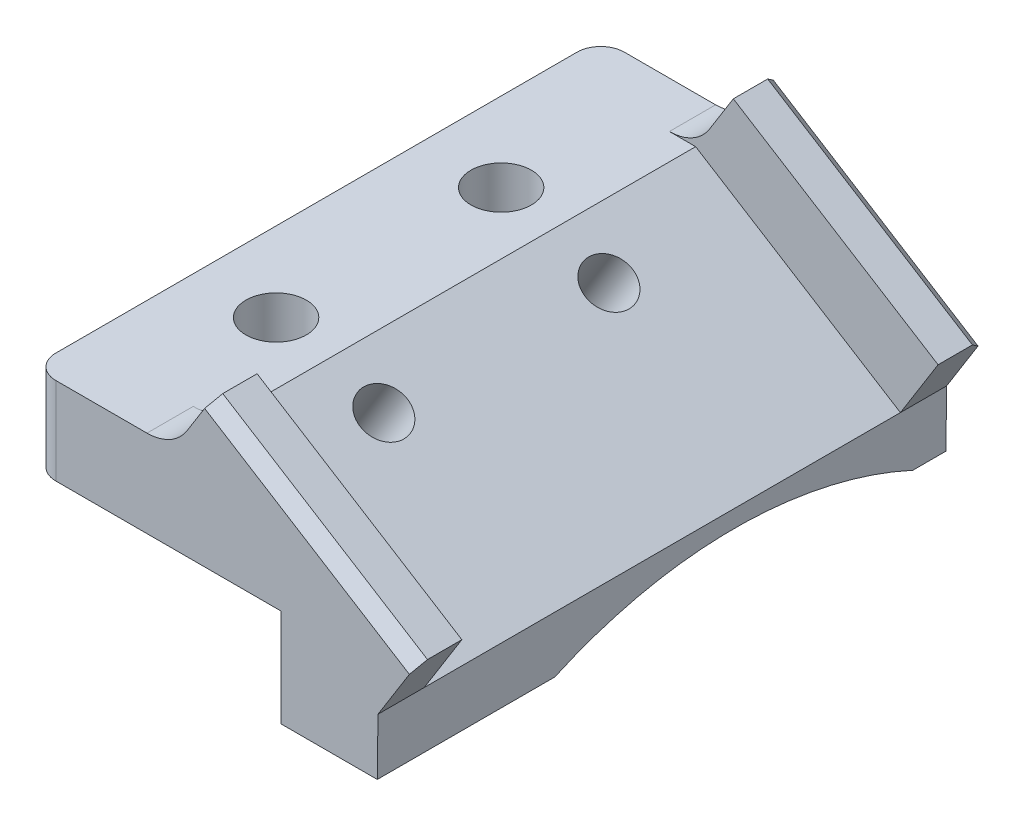
SolidWorks part; units mm, degrees
ref_plane "Front Plane" through (0, 0, 0) normal (0, 0, 1) x (1, 0, 0)
ref_plane "Top Plane" through (0, 0, 0) normal (0, 1, 0) x (1, 0, 0)
ref_plane "Right Plane" through (0, 0, 0) normal (1, 0, 0) x (0, 0, -1)
sketch "Sketch2" plane through (0, 0, 0) normal (0, 0, 1) x (1, 0, 0)
  line L0 (-14.571, 4.125) -> (-4.071, 4.125)
  line L1 (-4.071, 4.125) -> (-4.071, 0)
  line L2 (-4.071, 0) -> (0, 0)
  line L3 (0, 0) -> (0.0293, 2.4)
  line L4 (0.0293, 2.4) -> (-8.6125, 7.8)
  line L5 (-8.6125, 7.8) -> (-14.571, 7.8)
  line L6 (-14.571, 7.8) -> (-14.571, 4.125)
  dimension "D1" = 0.7
  dimension "D2" = 4.071
  dimension "D3" = 10.5
  dimension "D4" = 4.125
  dimension "D5" = 32
  dimension "D6" = 7.8
  dimension "D7" = 2.4
extrude "Boss-Extrude1" add sketch "Sketch2" along normal blind 24
sketch "Sketch3" plane through (1.0868, 1.7392, 0) normal (0.5299, 0.848, 0) x (0.848, -0.5299, 0)
  line L0 (-1.2469, -24) -> (-1.2469, 0) construction
  line L1 (-11.4372, 0) -> (-1.2469, 0)
  line L2 (-11.4372, 0) -> (-11.4372, -1.95)
  line L3 (-11.4372, -1.95) -> (-1.2469, -1.95)
  line L4 (-1.2469, 0) -> (-1.2469, -1.95)
  line L6 (-11.4372, -24) -> (-1.2469, -24)
  line L7 (-11.4372, -24) -> (-11.4372, -22.05)
  line L8 (-11.4372, -22.05) -> (-1.2469, -22.05)
  line L9 (-1.2469, -24) -> (-1.2469, -22.05)
  dimension "D1" = 20.1
  dimension "D2" = 1.95
  dimension "D3" = 1.95
extrude "Boss-Extrude2" add sketch "Sketch3" along normal blind 3
sketch "Sketch5" plane through (0, 0, 0) normal (0.9999, -0.0122, 0) x (0, 0, -1)
  line L0 (-24, 0) -> (0, 0) construction
  line L2 (0, 4.9636) -> (0, 2.4002) construction
  circle A0 centre (-8.95, -16.338) radius 18
  dimension "D1" = 36
  dimension "D2" = 16.338
  dimension "D3" = 8.95
extrude "Cut-Extrude1" cut sketch "Sketch5" against normal through all
chamfer "Chamfer1" distance 0.5 angle 45 2 edges at (-2.7018, 7.6441, 0) (-2.7018, 7.6441, 24)
fillet "Fillet1" radius 1 2 edges at (-14.571, 5.9625, 0) (-14.571, 5.9625, 24)
sketch "Sketch6" plane through (0, 7.8, 0) normal (0, 1, 0) x (1, 0, 0)
  line L0 (-8.6125, 0) -> (-13.571, 0) construction
  line L1 (-14.571, -23) -> (-14.571, -1) construction
  circle A0 centre (-11.221, -17.05) radius 1.275
  circle A1 centre (-11.221, -7.55) radius 1.275
  dimension "D1" = 2.55
  dimension "D2" = 2.55
  dimension "D3" = 9.5
  dimension "D4" = 7.55
  dimension "D5" = 3.35
extrude "Cut-Extrude2" cut sketch "Sketch6" against normal through all
sketch "Sketch7" plane through (2.6765, 4.2834, 0) normal (0.5299, 0.848, 0) x (0.848, -0.5299, 0)
  line L0 (-11.4372, 0) -> (-1.2469, 0) construction
  line L1 (-1.2469, -22.05) -> (-1.2469, -1.95) construction
  circle A0 centre (-9.1511, -17.05) radius 1
  circle A1 centre (-9.1511, -7.55) radius 1
  dimension "D1" = 2
  dimension "D2" = 2
  dimension "D3" = 9.5
  dimension "D4" = 7.55
  dimension "D5" = 7.9041
extrude "Cut-Extrude3" cut sketch "Sketch7" against normal through all
fillet "Fillet2" radius 2 2 edges at (-8.6125, 7.8, 23.025) (-8.6125, 7.8, 0.975)
